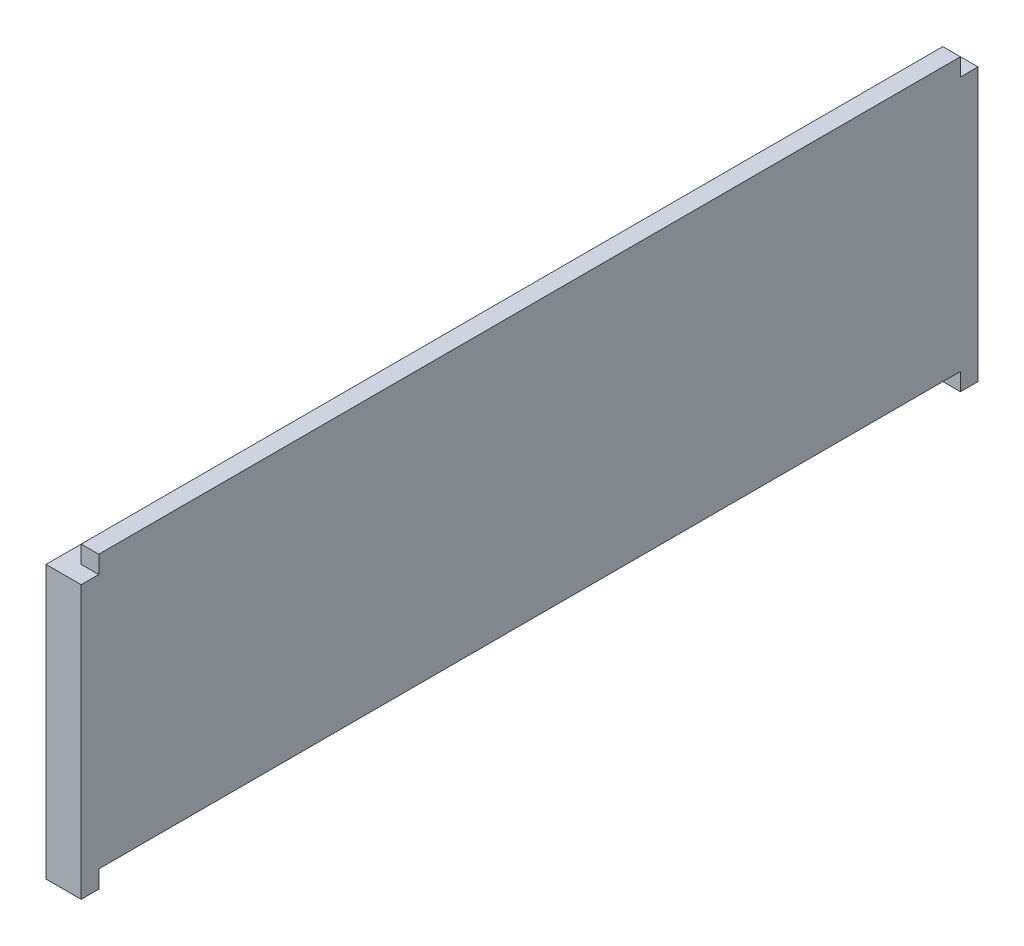
SolidWorks part; units mm, degrees
material "Сосна"
ref_plane "Спереди" through (0, 0, 0) normal (0, 0, 1) x (1, 0, 0)
ref_plane "Сверху" through (0, 0, 0) normal (0, 1, 0) x (1, 0, 0)
ref_plane "Справа" through (0, 0, 0) normal (1, 0, 0) x (0, 0, -1)
sketch "Эскиз1" plane through (0, 0, 0) normal (0, 0, 1) x (1, 0, 0)
  line L0 (0, 0) -> (0, 155)
  line L1 (0, 155) -> (10, 155)
  line L2 (10, 155) -> (10, 165)
  line L3 (10, 165) -> (20, 165)
  line L4 (20, 165) -> (20, 10)
  line L5 (20, 10) -> (10, 10)
  line L6 (10, 10) -> (10, 0)
  line L7 (10, 0) -> (0, 0)
  dimension "D1" = 155
  dimension "D2" = 10
  dimension "D3" = 10
  dimension "D4" = 20
  dimension "D5" = 10
  dimension "D6" = 10
extrude "Бобышка-Вытянуть1" add sketch "Эскиз1" along normal blind 490
sketch "Эскиз2" plane through (0, 0, 490) normal (0, 0, 1) x (1, 0, 0)
  line L0 (20, 165) -> (10, 165) construction
  line L1 (0, 0) -> (20, 0)
  line L2 (0, 0) -> (0, 165)
  line L3 (0, 165) -> (20, 165)
  line L4 (20, 0) -> (20, 165)
  line L5 (20, 10) -> (20, 165) construction
extrude "Бобышка-Вытянуть2" add sketch "Эскиз2" along normal blind 10
sketch "Эскиз3" plane through (0, 0, 0) normal (0, 0, -1) x (-1, 0, 0)
  line L2 (0, 0) -> (-20, 0)
  line L3 (0, 0) -> (0, 165)
  line L4 (0, 165) -> (-20, 165)
  line L5 (-20, 0) -> (-20, 165)
extrude "Бобышка-Вытянуть3" add sketch "Эскиз3" along normal blind 10
sketch "Эскиз4" plane through (20, 0, 0) normal (1, 0, 0) x (0, 0, -1)
  line L0 (10, 165) -> (10, 0) construction
  line L1 (-500, 165) -> (-490, 165)
  line L2 (-500, 165) -> (-500, 155)
  line L3 (-500, 155) -> (-490, 155)
  line L4 (-490, 165) -> (-490, 155)
  line L5 (10, 165) -> (0, 165)
  line L6 (10, 165) -> (10, 155)
  line L7 (10, 155) -> (0, 155)
  line L8 (0, 165) -> (0, 155)
  line L9 (-500, 165) -> (10, 165) construction
  dimension "D1" = 10
  dimension "D2" = 10
extrude "Вырез-Вытянуть1" cut sketch "Эскиз4" against normal through all
